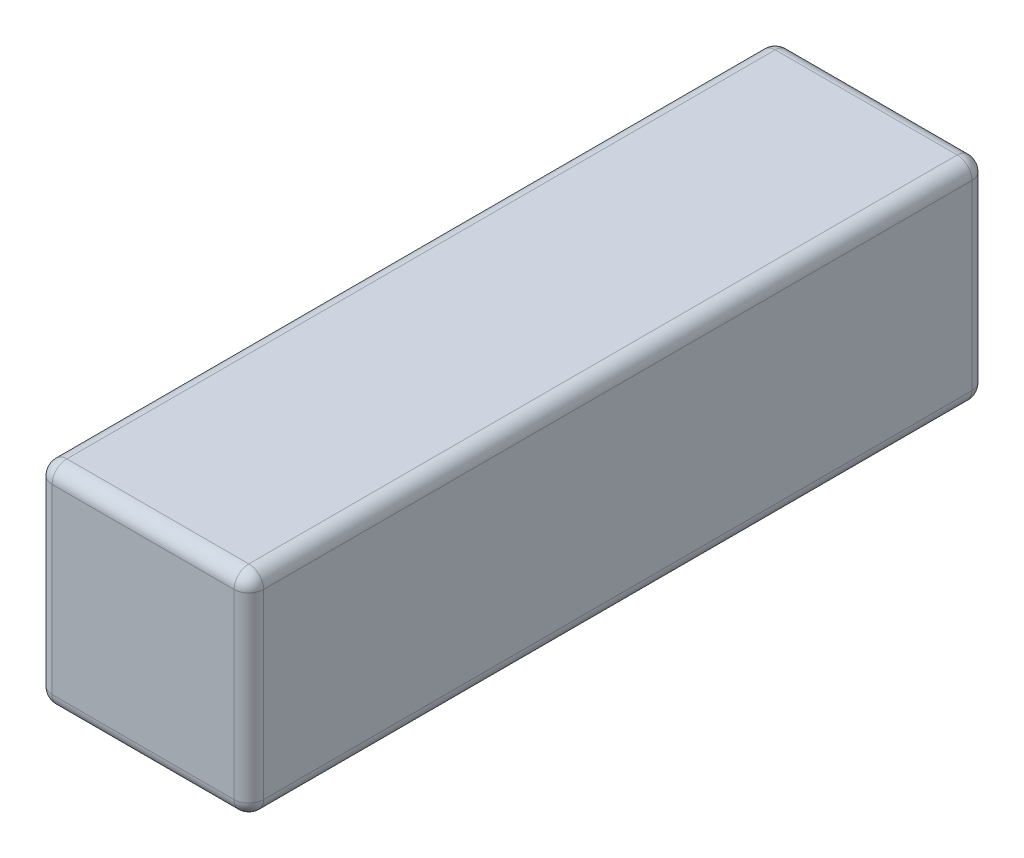
SolidWorks part; units mm, degrees
material "ABS"
ref_plane "前视基准面" through (0, 0, 0) normal (0, 0, 1) x (1, 0, 0)
ref_plane "上视基准面" through (0, 0, 0) normal (0, 1, 0) x (1, 0, 0)
ref_plane "右视基准面" through (0, 0, 0) normal (1, 0, 0) x (0, 0, -1)
other "Configuration Table"
sketch "草图1" plane through (0, 0, 0) normal (0, 1, 0) x (1, 0, 0)
  line L1 (-18.5, -75) -> (18.5, -75)
  line L2 (-21.5, -72) -> (-21.5, 72)
  line L3 (-18.5, 75) -> (18.5, 75)
  line L4 (21.5, -72) -> (21.5, 72)
  line L5 (-21.5, -75) -> (21.5, 75) construction
  line L6 (-21.5, 75) -> (21.5, -75) construction
  arc A0 (-21.5, -72) -> (-18.5, -75) centre (-18.5, -72) ccw
  arc A1 (21.5, -72) -> (18.5, -75) centre (18.5, -72) cw
  arc A2 (18.5, 75) -> (21.5, 72) centre (18.5, 72) cw
  arc A3 (-18.5, 75) -> (-21.5, 72) centre (-18.5, 72) ccw
  point P0 (0, 0)
  dimension "D3" = 3
  dimension "D1" = 43
  dimension "D2" = 150
extrude "凸台-拉伸1" add sketch "草图1" along normal mid plane 43
fillet "圆角1" radius 3 16 edges at (20.6213, -21.5, 74.1213) (0, -21.5, 75) (-20.6213, -21.5, 74.1213) (-21.5, -21.5, 0) (-20.6213, -21.5, -74.1213) (0, -21.5, -75) (20.6213, -21.5, -74.1213) (20.6213, 21.5, 74.1213) (0, 21.5, 75) (-20.6213, 21.5, 74.1213) (-21.5, 21.5, 0) (-20.6213, 21.5, -74.1213) (0, 21.5, -75) (20.6213, 21.5, -74.1213) (21.5, -21.5, 0) (21.5, 21.5, 0)
